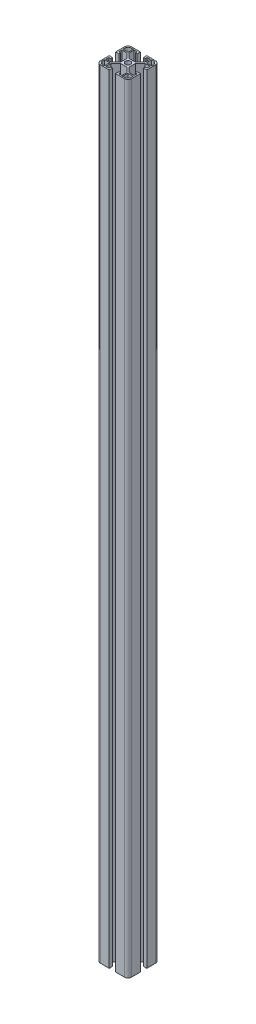
SolidWorks part; units mm, degrees
ref_plane "Front Plane" through (0, 0, 0) normal (0, 0, 1) x (1, 0, 0)
ref_plane "Top Plane" through (0, 0, 0) normal (0, 1, 0) x (1, 0, 0)
ref_plane "Right Plane" through (0, 0, 0) normal (1, 0, 0) x (0, 0, -1)
sketch "Sketch1" plane through (0, 0, 0) normal (0, 1, 0) x (1, 0, 0)
  line L1 (0, 0) -> (40, 0)
  line L2 (0, 0) -> (0, 40)
  line L3 (0, 40) -> (40, 40)
  line L4 (40, 0) -> (40, 40)
  dimension "D1" = 40
  dimension "D2" = 40
extrude "Boss-Extrude1" add sketch "Sketch1" along normal blind 1000
sketch "Sketch2" plane through (0, 1000, 0) normal (0, 1, 0) x (1, 0, 0)
  line L0 (30.25, 31.75) -> (24, 25.5)
  line L5 (30.25, 38.2) -> (30.25, 31.75)
  line L6 (26.4, 38.2) -> (30.25, 38.2)
  line L8 (26.4, 35.75) -> (26.4, 38.2)
  line L13 (24.1, 35.75) -> (26.4, 35.75)
  line L14 (24.1, 40) -> (24.1, 35.75)
  line L20 (40, 0) -> (40, 40) construction
  line L21 (31.75, 9.75) -> (25.5, 16)
  line L23 (0, 0) -> (40, 40) construction
  line L48 (38.2, 9.75) -> (31.75, 9.75)
  line L49 (38.2, 13.6) -> (38.2, 9.75)
  line L50 (35.75, 13.6) -> (38.2, 13.6)
  line L51 (35.75, 15.9) -> (35.75, 13.6)
  line L52 (40, 15.9) -> (35.75, 15.9)
  line L53 (40, 15.9) -> (40, 24.1)
  line L54 (40, 24.1) -> (35.75, 24.1)
  line L55 (35.75, 24.1) -> (35.75, 26.4)
  line L56 (24.1, 40) -> (15.9, 40)
  line L57 (40, 40) -> (0, 40) construction
  line L58 (15.9, 40) -> (15.9, 35.75)
  line L59 (15.9, 35.75) -> (13.6, 35.75)
  line L60 (13.6, 35.75) -> (13.6, 38.2)
  line L61 (13.6, 38.2) -> (9.75, 38.2)
  line L62 (9.75, 38.2) -> (9.75, 31.75)
  line L63 (9.75, 31.75) -> (16, 25.5)
  line L64 (16, 25.5) -> (24, 25.5)
  line L66 (0, 40) -> (0, 0) construction
  line L67 (8.45, 31.75) -> (1.5, 31.75)
  line L68 (8.45, 31.75) -> (8.45, 38.5)
  line L69 (8.45, 38.5) -> (1.5, 38.5)
  line L70 (1.5, 31.75) -> (1.5, 38.5)
  line L71 (35.75, 26.4) -> (38.2, 26.4)
  line L72 (38.2, 26.4) -> (38.2, 30.25)
  line L73 (38.2, 30.25) -> (31.75, 30.25)
  line L74 (31.75, 30.25) -> (25.5, 24)
  line L75 (25.5, 24) -> (25.5, 16)
  line L76 (31.75, 31.55) -> (31.75, 38.5)
  line L77 (31.75, 31.55) -> (38.5, 31.55)
  line L78 (38.5, 31.55) -> (38.5, 38.5)
  line L79 (31.75, 38.5) -> (38.5, 38.5)
  line L80 (9.75, 8.25) -> (16, 14.5)
  line L81 (9.75, 1.8) -> (9.75, 8.25)
  line L82 (13.6, 1.8) -> (9.75, 1.8)
  line L83 (13.6, 4.25) -> (13.6, 1.8)
  line L84 (15.9, 4.25) -> (13.6, 4.25)
  line L85 (15.9, 0) -> (15.9, 4.25)
  line L86 (15.9, 0) -> (24.1, 0)
  line L87 (24.1, 0) -> (24.1, 4.25)
  line L88 (24.1, 4.25) -> (26.4, 4.25)
  line L89 (26.4, 4.25) -> (26.4, 1.8)
  line L90 (26.4, 1.8) -> (30.25, 1.8)
  line L91 (30.25, 1.8) -> (30.25, 8.25)
  line L92 (30.25, 8.25) -> (24, 14.5)
  line L93 (24, 14.5) -> (16, 14.5)
  line L94 (31.55, 8.25) -> (38.5, 8.25)
  line L95 (31.55, 8.25) -> (31.55, 1.5)
  line L96 (31.55, 1.5) -> (38.5, 1.5)
  line L97 (38.5, 8.25) -> (38.5, 1.5)
  line L98 (8.25, 30.25) -> (14.5, 24)
  line L99 (1.8, 30.25) -> (8.25, 30.25)
  line L100 (1.8, 26.4) -> (1.8, 30.25)
  line L101 (4.25, 26.4) -> (1.8, 26.4)
  line L102 (4.25, 24.1) -> (4.25, 26.4)
  line L103 (0, 24.1) -> (4.25, 24.1)
  line L104 (0, 24.1) -> (0, 15.9)
  line L105 (0, 15.9) -> (4.25, 15.9)
  line L106 (4.25, 15.9) -> (4.25, 13.6)
  line L107 (4.25, 13.6) -> (1.8, 13.6)
  line L108 (1.8, 13.6) -> (1.8, 9.75)
  line L109 (1.8, 9.75) -> (8.25, 9.75)
  line L110 (8.25, 9.75) -> (14.5, 16)
  line L111 (14.5, 16) -> (14.5, 24)
  line L112 (8.25, 8.45) -> (8.25, 1.5)
  line L113 (8.25, 8.45) -> (1.5, 8.45)
  line L114 (1.5, 8.45) -> (1.5, 1.5)
  line L115 (8.25, 1.5) -> (1.5, 1.5)
  circle A0 centre (20, 20) radius 3.4
  point P26 (8.45, 35.125)
  point P47 (20, 20)
  point P89 (20, 20)
  dimension "D9" = 135
  dimension "D1" = 6.8
  dimension "D2" = 8.2
  dimension "D3" = 20.5
  dimension "D4" = 1.8
  dimension "D5" = 4.25
  dimension "D6" = 14.5
  dimension "D7" = 9.75
  dimension "D8" = 8.25
  dimension "D10" = 1.5
  dimension "D11" = 1.5
  dimension "D12" = 1.3
  dimension "D13" = 3.85
  dimension "D14" = 4.25
  dimension "D15" = 1.8
  dimension "D16" = 15.9
  dimension "D17" = 15.9
  dimension "D18" = 13.6
  dimension "D19" = 135
  dimension "D20" = 8.25
  dimension "D21" = 4
extrude "Cut-Extrude1" cut sketch "Sketch2" against normal through all
fillet "Fillet1" radius 4.5 8 edges at (1.5, 500, -1.5) (0, 500, 0) (1.5, 500, -38.5) (0, 500, -40) (38.5, 500, -38.5) (40, 500, -40) (40, 500, 0) (38.5, 500, -1.5)
